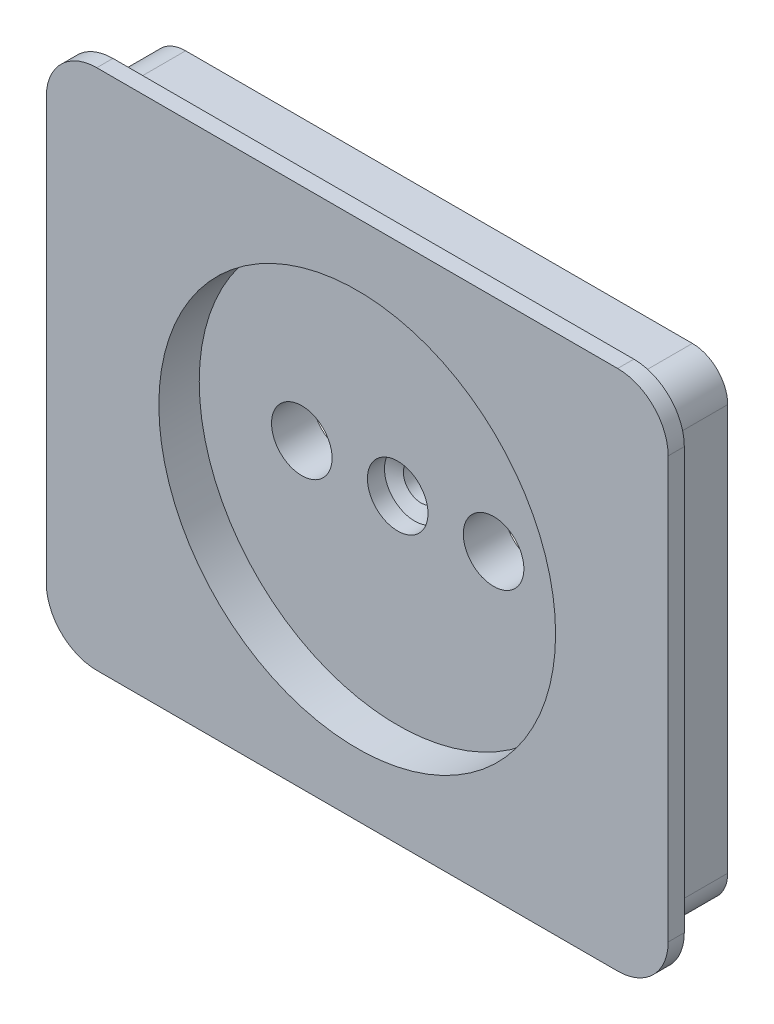
SolidWorks part; units mm, degrees
ref_plane "Front Plane" through (0, 0, 0) normal (0, 0, 1) x (1, 0, 0)
ref_plane "Top Plane" through (0, 0, 0) normal (0, 1, 0) x (1, 0, 0)
ref_plane "Right Plane" through (0, 0, 0) normal (1, 0, 0) x (0, 0, -1)
sketch "Sketch1" plane through (0, 0, 0) normal (0, 0, 1) x (1, 0, 0)
  line L0 (-9.5, 0) -> (9.5, 0)
  line L1 (-28.6, 23.6) -> (28.6, 23.6)
  line L2 (-28.6, 23.6) -> (-28.6, -23.6)
  line L3 (-28.6, -23.6) -> (28.6, -23.6)
  line L4 (28.6, 23.6) -> (28.6, -23.6)
  line L5 (-28.6, 23.6) -> (28.6, -23.6) construction
  line L6 (-28.6, -23.6) -> (28.6, 23.6) construction
  circle A0 centre (0, 0) radius 1.75
  circle A1 centre (-9.5, 0) radius 3
  circle A2 centre (9.5, 0) radius 3
  point P0 (0, 0)
  point P16 (0, 0)
  dimension "D3" = 6
  dimension "D5" = 3.5
  dimension "D1" = 57.2
  dimension "D2" = 47.2
  dimension "D4" = 19
extrude "Boss-Extrude1" add sketch "Sketch1" along normal blind 8.1
sketch "Sketch2" plane through (0, 0, 8.1) normal (0, 0, 1) x (1, 0, 0)
  circle A0 centre (0, 0) radius 19.65
  dimension "D1" = 39.3
extrude "Cut-Extrude1" cut sketch "Sketch2" against normal blind 4
sketch "Sketch3" plane through (0, 0, 4.1) normal (0, 0, 1) x (1, 0, 0)
  circle A0 centre (0, 0) radius 3
  dimension "D1" = 6
extrude "Cut-Extrude2" cut sketch "Sketch3" against normal blind 1.7
sketch "Sketch4" plane through (0, 0, 0) normal (0, 1, 0) x (1, 0, 0)
  line L1 (-3, -2.4) -> (3, -2.4) construction
  line L2 (0, -2.4) -> (0, -0.9)
  line L3 (0, -0.9) -> (3, -2.4)
  line L4 (0, -2.4) -> (3, -2.4)
  line L6 (-3, -2.4) -> (3, -2.4) construction
  dimension "D1" = 1.5
revolve "Cut-Revolve1" cut sketch "Sketch4" angle 360 about L2
sketch "Sketch5" plane through (0, 0, 8.1) normal (0, 0, 1) x (1, 0, 0)
  line L0 (30.8, 0) -> (-30.8, 0) construction
  line L1 (0, 25.85) -> (0, -25.85) construction
  line L3 (-28.6, 23.6) -> (28.6, 23.6)
  line L4 (28.6, 23.6) -> (28.6, -23.6)
  line L5 (28.6, -23.6) -> (-28.6, -23.6)
  line L6 (-28.6, -23.6) -> (-28.6, 23.6)
  line L7 (-30.8, 0) -> (-30.8, -25.85)
  line L12 (-30.8, -25.85) -> (30.8, -25.85)
  line L13 (30.8, -25.85) -> (30.8, 25.85)
  line L14 (30.8, 25.85) -> (-30.8, 25.85)
  line L15 (-30.8, 25.85) -> (-30.8, 0)
  point P9 (0, 0)
  point P15 (0, 0)
  dimension "D2" = 51.7
  dimension "D3" = 61.6
extrude "Boss-Extrude2" add sketch "Sketch5" against normal blind 1.6
fillet "Fillet1" radius 3.5 4 edges at (-28.6, -23.6, 3.25) (28.6, -23.6, 3.25) (28.6, 23.6, 3.25) (-28.6, 23.6, 3.25)
fillet "Fillet2" radius 5 4 edges at (-30.8, 25.85, 7.3) (30.8, 25.85, 7.3) (30.8, -25.85, 7.3) (-30.8, -25.85, 7.3)
sketch "Sketch9" plane through (0, 0, 4.1) normal (0, 0, 1) x (1, 0, 0)
  line L0 (19.4903, 2.5) -> (25, 2.5) construction
  line L1 (-25, 2.5) -> (-19.4903, 2.5) construction
  line L2 (-25, 2.5) -> (-25, -2.5) construction
  line L3 (-25, -2.5) -> (-19.4903, -2.5) construction
  line L4 (25, 2.5) -> (25, -2.5) construction
  line L5 (-25, 2.5) -> (25, -2.5) construction
  line L6 (-25, -2.5) -> (25, 2.5) construction
  line L7 (19.4903, -2.5) -> (25, -2.5) construction
  line L20 (-26, 3.5) -> (-20.3512, 3.5)
  line L21 (-26, 3.5) -> (-26, -3.5)
  line L22 (-26, -3.5) -> (-20.3512, -3.5)
  line L23 (20.3512, -3.5) -> (26, -3.5)
  line L24 (26, 3.5) -> (26, -3.5)
  line L25 (20.3512, 3.5) -> (26, 3.5)
  line L26 (-26.17, 3.67) -> (-20.494, 3.67)
  line L27 (-26.17, 3.67) -> (-26.17, -3.67)
  line L28 (-26.17, -3.67) -> (-20.494, -3.67)
  line L29 (20.494, -3.67) -> (26.17, -3.67)
  line L30 (26.17, 3.67) -> (26.17, -3.67)
  line L31 (20.494, 3.67) -> (26.17, 3.67)
  arc A0 (19.4903, 2.5) -> (-19.4903, 2.5) centre (0, 0) ccw construction
  circle A1 centre (0, 0) radius 19.65
  arc A2 (-19.4903, -2.5) -> (19.4903, -2.5) centre (0, 0) ccw construction
  arc A7 (20.3512, 3.5) -> (-20.3512, 3.5) centre (0, 0) ccw
  arc A8 (-20.3512, -3.5) -> (20.3512, -3.5) centre (0, 0) ccw
  arc A9 (20.494, 3.67) -> (-20.494, 3.67) centre (0, 0) ccw
  arc A10 (-20.494, -3.67) -> (20.494, -3.67) centre (0, 0) ccw
  dimension "D2" = 50
  dimension "D3" = 5
  dimension "D1" = 0
  dimension "D4" = 1
  dimension "D5" = 0.17
extrude "Cut-Extrude7" cut sketch "Sketch9" against normal through all
sketch "Sketch11" plane through (0, 0, 4.1) normal (0, 0, 1) x (1, 0, 0)
  line L0 (20.494, -3.67) -> (26.17, -3.67) construction
  line L1 (26.17, 3.67) -> (26.17, -3.67) construction
  line L2 (20.494, 3.67) -> (26.17, 3.67) construction
  line L3 (-26.17, -3.67) -> (-20.494, -3.67) construction
  line L4 (-26.17, 3.67) -> (-26.17, -3.67) construction
  line L5 (-26.17, 3.67) -> (-20.494, 3.67) construction
  line L6 (20.494, -3.67) -> (26.17, -3.67)
  line L7 (26.17, 3.67) -> (26.17, -3.67)
  line L8 (20.494, 3.67) -> (26.17, 3.67)
  line L9 (-26.17, -3.67) -> (-20.494, -3.67)
  line L10 (-26.17, 3.67) -> (-26.17, -3.67)
  line L11 (-26.17, 3.67) -> (-20.494, 3.67)
  arc A0 (-20.494, -3.67) -> (20.494, -3.67) centre (0, 0) ccw construction
  arc A1 (20.494, 3.67) -> (-20.494, 3.67) centre (0, 0) ccw construction
  arc A2 (-20.494, -3.67) -> (20.494, -3.67) centre (0, 0) ccw
  arc A3 (20.494, 3.67) -> (-20.494, 3.67) centre (0, 0) ccw
extrude "Cut-Extrude8" cut sketch "Sketch11" against normal blind 0.01
